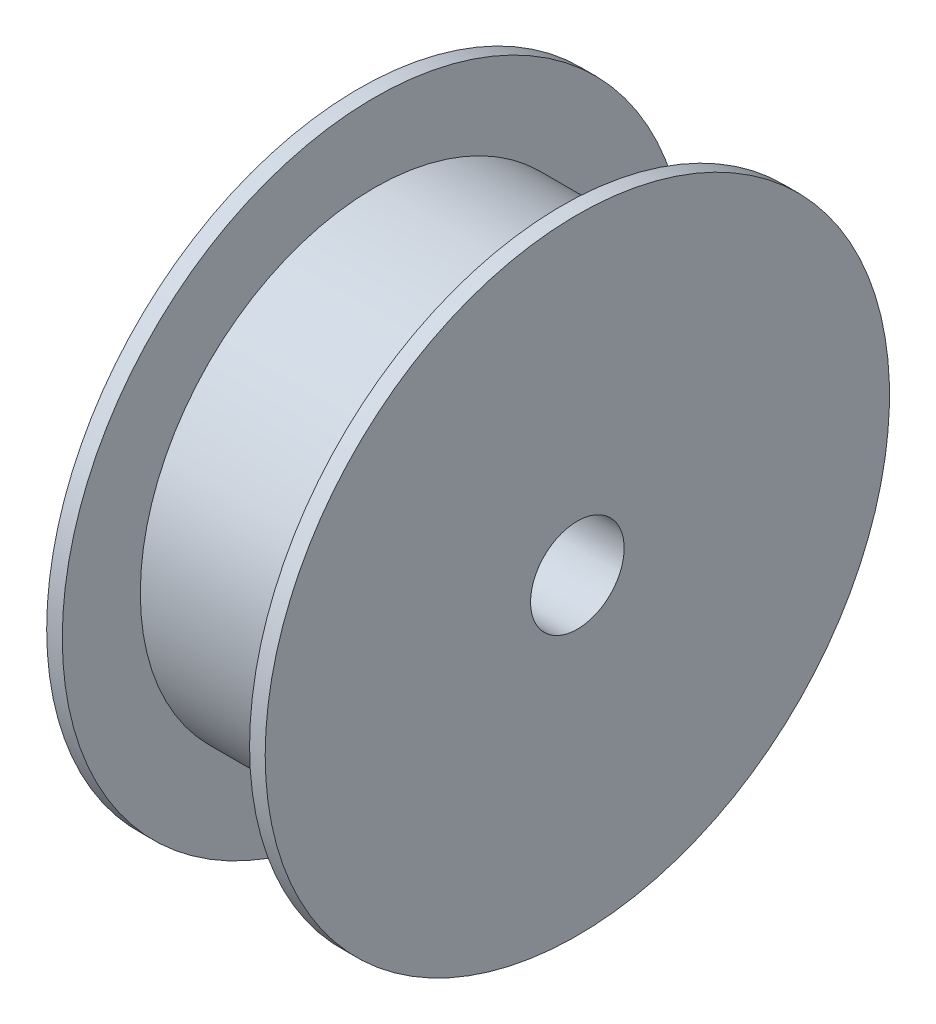
SolidWorks part; units mm, degrees
material "6061 合金"
ref_plane "正面" through (0, 0, 0) normal (0, 0, 1) x (1, 0, 0)
ref_plane "平面" through (0, 0, 0) normal (0, 1, 0) x (1, 0, 0)
ref_plane "右側面" through (0, 0, 0) normal (1, 0, 0) x (0, 0, -1)
sketch "ｽｹｯﾁ2" plane through (0, 0, 0) normal (0, 1, 0) x (1, 0, 0)
  line L0 (-44.7309, -0.056) -> (-44.7309, -17.056)
  line L1 (-44.7309, -0.056) -> (-43.7309, -0.056)
  line L2 (-43.7309, -0.056) -> (-43.7309, -5.056)
  line L3 (-43.7309, -5.056) -> (-31.7309, -5.056)
  line L4 (-31.7309, -5.056) -> (-31.7309, -0.056)
  line L5 (-31.7309, -0.056) -> (-30.7309, -0.056)
  line L6 (-30.7309, -0.056) -> (-30.7309, -17.056)
  line L7 (-30.7309, -17.056) -> (-44.7309, -17.056)
  line L8 (-49.8494, -20.056) -> (-18.0543, -20.056) construction
  dimension "D1" = 1
  dimension "D2" = 1
  dimension "D3" = 5
  dimension "D4" = 5
  dimension "D5" = 17
  dimension "D6" = 14
  dimension "D7" = 3
revolve "回転1" add sketch "ｽｹｯﾁ2" angle 360 about L8
sketch "ｽｹｯﾁ3" plane through (0, 0, 0) normal (0, 1, 0) x (1, 0, 0)
  line L1 (-43.7309, -0.056) -> (-44.7309, -0.056) construction
  line L2 (-30.7309, -40.056) -> (-30.7309, -0.056) construction
  circle A0 centre (-37.7309, -20.056) radius 1.6
  dimension "D1" = 3.2
  dimension "D2" = 20
  dimension "D3" = 7
extrude "ｶｯﾄ - 押し出し1" cut sketch "ｽｹｯﾁ3" against normal through all
